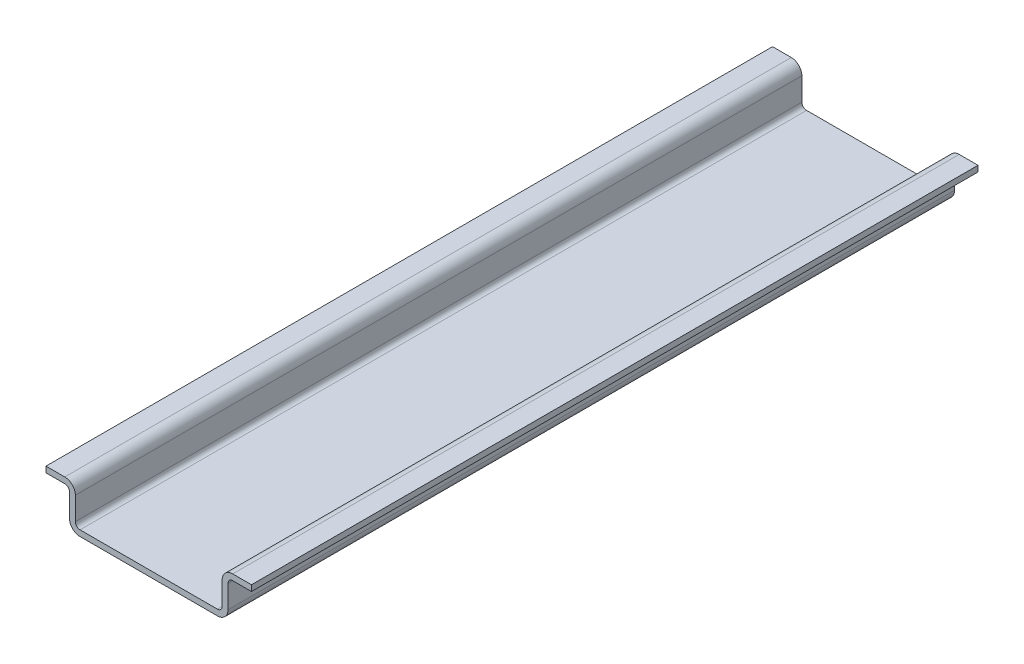
SolidWorks part; units mm, degrees
material "PVC 0.007 Plasticized"
material "PVC 0.007 Plasticized"
ref_plane "Front" through (0, 0, 0) normal (0, 0, 1) x (1, 0, 0)
ref_plane "Top" through (0, 0, 0) normal (0, 1, 0) x (1, 0, 0)
ref_plane "Right" through (0, 0, 0) normal (1, 0, 0) x (0, 0, -1)
sketch "Sketch1" plane through (0, 0, 0) normal (0, 1, 0) x (1, 0, 0)
  line L0 (0, 0) -> (0, 123.75)
  dimension "D1" = 123.75
other "Din_rail NS 35 7 5 PERF 2000MM(1)"
ref_plane "Plane1" through (0, 0, 0) normal (0, 0, -1) x (-1, 0, 0)
sketch "Sketch12" plane through (0, 0, 0) normal (0, 0, -1) x (-1, 0, 0)
  line L0 (11.7, 0) -> (-11.7, 0)
  line L1 (-13.5, 1.8) -> (-13.5, 5.7)
  line L2 (-14.3, 6.5) -> (-17.5, 6.5)
  line L3 (-17.5, 6.5) -> (-17.5, 7.5)
  line L4 (-17.5, 7.5) -> (-14.3, 7.5)
  line L5 (-12.5, 5.7) -> (-12.5, 1.8)
  line L6 (-11.7, 1) -> (11.7, 1)
  line L7 (0, 1) -> (0, 0) construction
  line L8 (12.5, 5.7) -> (12.5, 1.8)
  line L9 (17.5, 7.5) -> (14.3, 7.5)
  line L10 (17.5, 6.5) -> (17.5, 7.5)
  line L11 (14.3, 6.5) -> (17.5, 6.5)
  line L12 (13.5, 1.8) -> (13.5, 5.7)
  line L13 (12.5, 5.7) -> (0, 0) construction
  line L14 (0, 0) -> (-12.5, 5.7) construction
  arc A0 (-14.3, 7.5) -> (-12.5, 5.7) centre (-14.3, 5.7) cw
  arc A1 (-14.3, 6.5) -> (-13.5, 5.7) centre (-14.3, 5.7) cw
  arc A2 (-12.5, 1.8) -> (-11.7, 1) centre (-11.7, 1.8) ccw
  arc A3 (-11.7, 0) -> (-13.5, 1.8) centre (-11.7, 1.8) cw
  arc A4 (11.7, 0) -> (13.5, 1.8) centre (11.7, 1.8) ccw
  arc A5 (12.5, 1.8) -> (11.7, 1) centre (11.7, 1.8) cw
  arc A6 (14.3, 6.5) -> (13.5, 5.7) centre (14.3, 5.7) ccw
  arc A7 (14.3, 7.5) -> (12.5, 5.7) centre (14.3, 5.7) ccw
  point P2 (-13.5, 3.75)
  point P9 (0, 0)
  dimension "D7" = 1.8
  dimension "D8" = 0.8
  dimension "D9" = 0.8
  dimension "D10" = 1.8
  dimension "D1" = 13.5
  dimension "D2" = 4
  dimension "D3" = 7.5
  dimension "D4" = 1
  dimension "D5" = 1
  dimension "D6" = 1
